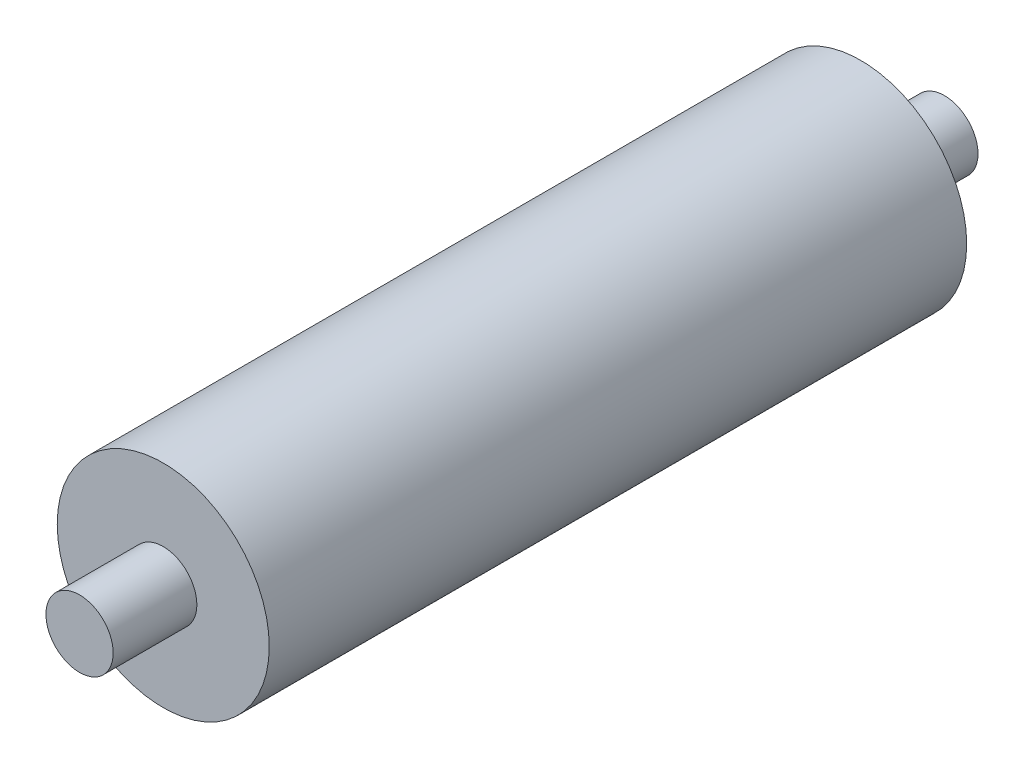
SolidWorks part; units mm, degrees
ref_plane "Front Plane" through (0, 0, 0) normal (0, 0, 1) x (1, 0, 0)
ref_plane "Top Plane" through (0, 0, 0) normal (0, 1, 0) x (1, 0, 0)
ref_plane "Right Plane" through (0, 0, 0) normal (1, 0, 0) x (0, 0, -1)
sketch "Sketch1" plane through (0, 0, 0) normal (0, 0, 1) x (1, 0, 0)
  circle A0 centre (0, 0) radius 14
  circle A1 centre (0, 0) radius 19
  dimension "D1" = 28
  dimension "D2" = 38
extrude "Boss-Extrude1" add sketch "Sketch1" against normal blind 125
ref_plane "Plane1" through (0, 0, -7.5) normal (0, 0, 1) x (1, 0, 0)
sketch "Sketch2" plane through (0, 0, -7.5) normal (0, 0, 1) x (1, 0, 0)
  circle A0 centre (0, 0) radius 14
  circle A1 centre (0, 0) radius 14 construction
extrude "Boss-Extrude2" add sketch "Sketch2" along normal up to surface (7.5 mm away) up to face at (14, 0, 0)
sketch "Sketch4" plane through (0, 0, -7.5) normal (0, 0, 1) x (1, 0, 0)
  circle A0 centre (0, 0) radius 6.025
  circle A1 centre (0, 0) radius 14 construction
  dimension "D1" = 12.05
extrude "Cut-Extrude1" cut sketch "Sketch4" against normal through all both and the other way through all
ref_plane "Plane2" through (0, 0, -117.5) normal (0, 0, -1) x (-1, 0, 0)
sketch "Sketch5" plane through (0, 0, -117.5) normal (0, 0, -1) x (-1, 0, 0)
  circle A0 centre (0, 0) radius 14
  circle A1 centre (0, 0) radius 14 construction
extrude "Boss-Extrude3" add sketch "Sketch5" along normal blind 7.5
sketch "Sketch7" plane through (0, 0, 0) normal (0, 0, 1) x (1, 0, 0)
  circle A0 centre (0, 0) radius 6.025
  circle A1 centre (0, 0) radius 6.025 construction
extrude "Boss-Extrude4" add sketch "Sketch7" along normal blind 15 and the other way blind 140
sketch "Sketch8" plane through (0, 0, 0) normal (0, 1, 0) x (1, 0, 0)
  line L0 (0, 127.5) -> (0, 125) construction
  line L1 (0, 127.5) -> (-6.025, 127.5) construction
  line L2 (0, 127.5) -> (6.025, 127.5) construction
  line L3 (19, 125) -> (-19, 125) construction
  line L4 (-6.025, 140) -> (-6.025, 125) construction
  line L5 (6.025, 125) -> (6.025, 140) construction
  circle A0 centre (0, 127.5) radius 1.5
  dimension "D1" = 3
  dimension "D2" = 2.5
extrude "Cut-Extrude2" cut sketch "Sketch8" against normal through all both and the other way through all
sketch "Sketch9" plane through (0, 0, -140) normal (0, 0, -1) x (-1, 0, 0)
  circle A0 centre (0, 0) radius 3.5
  circle A2 centre (0, 0) radius 6.025 construction
  dimension "D1" = 7
extrude "Cut-Extrude3" cut sketch "Sketch9" against normal blind 22
ref_plane "Plane3" through (0, 0, -62.5) normal (0, 0, -1) x (-1, 0, 0)
sketch "Sketch11" plane through (0, 0, -62.5) normal (0, 0, -1) x (-1, 0, 0)
  circle A0 centre (0, 0) radius 15
  point P2 (0, 0)
  dimension "D1" = 30
extrude "Boss-Extrude5" add sketch "Sketch11" along normal blind 5 and the other way blind 5
pattern_linear "LPattern1" count 2 spacing 30 along (0, 0, -1) of "Boss-Extrude5"
pattern_linear "LPattern2" count 2 spacing 30 along (0, 0, 1) of "LPattern1"
